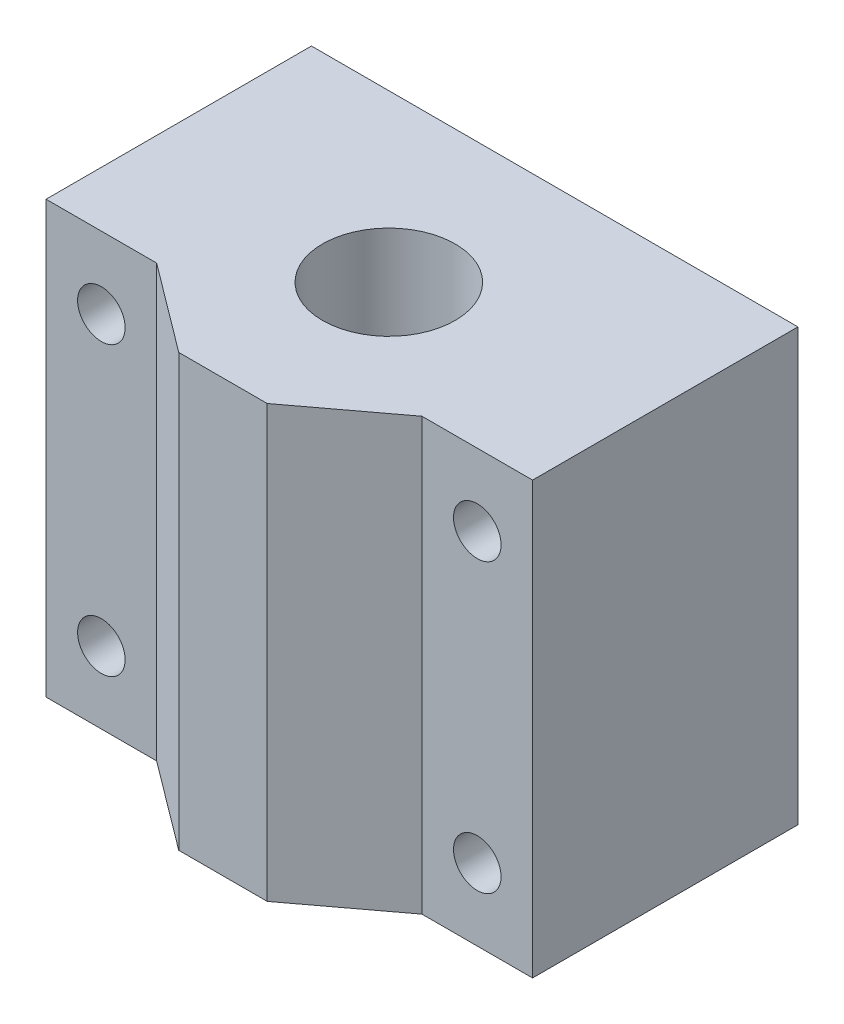
SolidWorks part; units mm, degrees
ref_plane "Front Plane" through (0, 0, 0) normal (0, 0, 1) x (1, 0, 0)
ref_plane "Top Plane" through (0, 0, 0) normal (0, 1, 0) x (1, 0, 0)
ref_plane "Right Plane" through (0, 0, 0) normal (1, 0, 0) x (0, 0, -1)
sketch "Sketch1" plane through (0, 0, 0) normal (0, 1, 0) x (1, 0, 0)
  line L0 (21.3999, 28.6496) -> (-22.6001, 28.6496)
  line L1 (-22.6001, 28.6496) -> (-22.6001, 4.6496)
  line L2 (-22.6001, 4.6496) -> (-12.6001, 4.6496)
  line L3 (-12.6001, 4.6496) -> (-4.6001, -1.3504)
  line L4 (-4.6001, -1.3504) -> (3.3999, -1.3504)
  line L5 (-0.6001, 28.6496) -> (-0.6001, -10.2577) construction
  line L6 (11.3999, 4.6496) -> (3.3999, -1.3504)
  line L7 (21.3999, 4.6496) -> (11.3999, 4.6496)
  line L8 (21.3999, 28.6496) -> (21.3999, 4.6496)
  circle A0 centre (-0.6001, 13.6496) radius 6
  point P8 (-0.6001, -1.3504)
  dimension "D6" = 12
  dimension "D1" = 22
  dimension "D2" = 30
  dimension "D3" = 24
  dimension "D4" = 10
  dimension "D5" = 15
  dimension "D7" = 8
extrude "Boss-Extrude1" add sketch "Sketch1" along normal blind 39
sketch "Sketch2" plane through (0, 0, -4.6496) normal (0, 0, 1) x (1, 0, 0)
  line L0 (-22.6001, 0) -> (-12.6001, 0) construction
  line L2 (-22.6001, 39) -> (-22.6001, 0) construction
  line L3 (-0.6001, 42.2937) -> (-0.6001, -2.1287) construction
  line L4 (21.3999, 39) -> (21.3999, 0) construction
  circle A0 centre (-17.6001, 32.5) radius 2.15
  circle A1 centre (-17.6001, 6.5) radius 2.15
  circle A2 centre (16.3999, 6.5) radius 2.15
  circle A3 centre (16.3999, 32.5) radius 2.15
  dimension "D2" = 4.3
  dimension "D1" = 26
  dimension "D3" = 6.5
  dimension "D4" = 5
  dimension "D5" = 5
  dimension "D6" = 22
extrude "Cut-Extrude1" cut sketch "Sketch2" against normal through all
sketch "Sketch3" plane through (0, 0, -28.6496) normal (0, 0, -1) x (-1, 0, 0)
  circle A0 centre (-16.3999, 32.5) radius 4
  circle A1 centre (17.6001, 32.5) radius 4
  circle A2 centre (17.6001, 6.5) radius 4
  circle A3 centre (-16.3999, 6.5) radius 4
  dimension "D1" = 8
